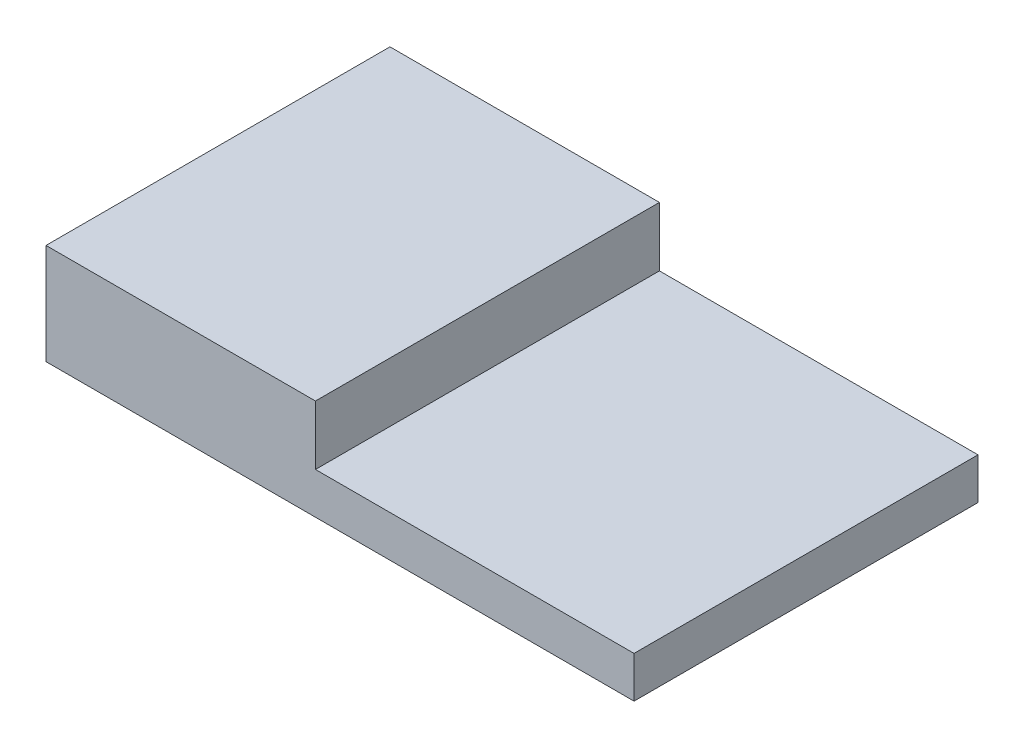
SolidWorks part; units mm, degrees
ref_plane "Front Plane" through (0, 0, 0) normal (0, 0, 1) x (1, 0, 0)
ref_plane "Top Plane" through (0, 0, 0) normal (0, 1, 0) x (1, 0, 0)
ref_plane "Right Plane" through (0, 0, 0) normal (1, 0, 0) x (0, 0, -1)
sketch "Sketch1" plane through (0, 0, 0) normal (0, 0, 1) x (1, 0, 0)
  line L0 (0, 18.5857) -> (0, 0)
  line L1 (0, 0) -> (108.5582, 0)
  line L2 (108.5582, 0) -> (108.5582, 7.638)
  line L3 (108.5582, 7.638) -> (49.7458, 7.638)
  line L4 (49.7458, 7.638) -> (49.7458, 18.5857)
  line L5 (49.7458, 18.5857) -> (0, 18.5857)
extrude "Extrude1" add sketch "Sketch1" against normal blind 63.5
ref_plane "Plane1" through (0, 0, 0) normal (0, 0, -1) x (-1, 0, 0)
